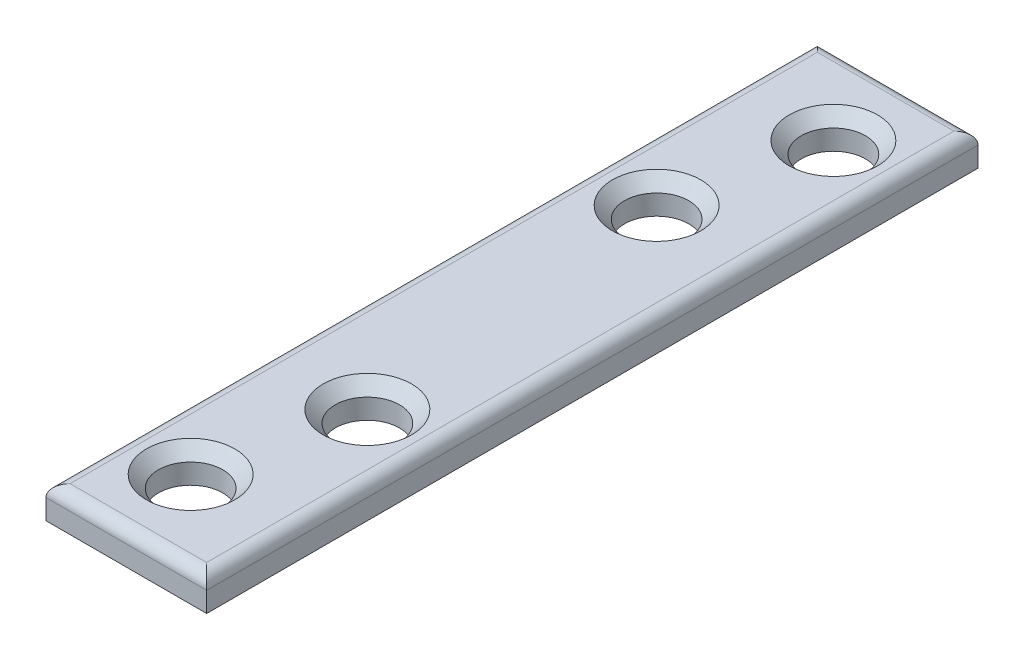
SolidWorks part; units mm, degrees
ref_plane "Front Plane" through (0, 0, 0) normal (0, 0, 1) x (1, 0, 0)
ref_plane "Top Plane" through (0, 0, 0) normal (0, 1, 0) x (1, 0, 0)
ref_plane "Right Plane" through (0, 0, 0) normal (1, 0, 0) x (0, 0, -1)
sketch "Sketch1" plane through (0, 0, 0) normal (0, 1, 0) x (1, 0, 0)
  line L0 (15.875, 38.1) -> (0, 38.1) construction
  line L1 (0, 0) -> (15.875, 0)
  line L2 (0, 0) -> (0, 76.2)
  line L3 (0, 76.2) -> (15.875, 76.2)
  line L4 (15.875, 0) -> (15.875, 76.2)
  dimension "D1" = 15.875
  dimension "D2" = 76.2
extrude "Boss-Extrude1" add sketch "Sketch1" along normal blind 3.175
sketch "Sketch2" plane through (0, 3.175, 0) normal (0, 1, 0) x (1, 0, 0)
  line L0 (0, 76.2) -> (0, 0) construction
  line L1 (15.875, 0) -> (15.875, 76.2) construction
  line L2 (15.875, 76.2) -> (0, 76.2) construction
  line L3 (0, 0) -> (15.875, 0) construction
  circle A0 centre (6.35, 53.975) radius 3.175
  circle A1 centre (9.525, 68.2625) radius 3.175
  circle A2 centre (9.525, 22.225) radius 3.175
  circle A3 centre (6.35, 7.9375) radius 3.175
  dimension "D1" = 6.35
  dimension "D2" = 6.35
  dimension "D3" = 6.35
  dimension "D4" = 6.35
  dimension "D5" = 6.35
  dimension "D6" = 6.35
  dimension "D7" = 7.9375
  dimension "D8" = 22.225
  dimension "D9" = 22.225
  dimension "D10" = 6.35
  dimension "D11" = 6.35
  dimension "D12" = 7.9375
extrude "Cut-Extrude1" cut sketch "Sketch2" against normal through all
chamfer "Chamfer1" distance 1.1906 angle 45 4 edges at (6.35, 3.175, -4.7625) (9.525, 3.175, -19.05) (9.525, 3.175, -65.0875) (6.35, 3.175, -50.8)
fillet "Fillet1" radius 1.1906 4 edges at (7.9375, 3.175, -76.2) (15.875, 3.175, -38.1) (7.9375, 3.175, 0) (0, 3.175, -38.1)
